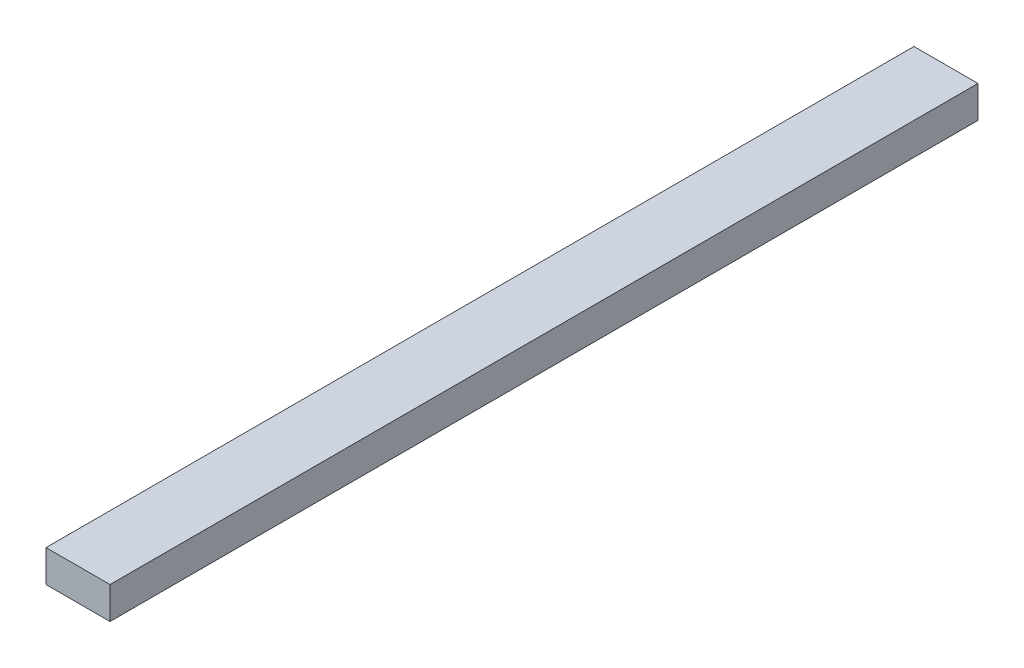
SolidWorks part; units mm, degrees
ref_plane "Front Plane" through (0, 0, 0) normal (0, 0, 1) x (1, 0, 0)
ref_plane "Top Plane" through (0, 0, 0) normal (0, 1, 0) x (1, 0, 0)
ref_plane "Right Plane" through (0, 0, 0) normal (1, 0, 0) x (0, 0, -1)
sketch "Sketch1" plane through (0, 0, 0) normal (0, 0, 1) x (1, 0, 0)
  line L1 (0, 0) -> (40, 0)
  line L2 (0, 0) -> (0, 20)
  line L3 (0, 20) -> (40, 20)
  line L4 (40, 0) -> (40, 20)
  dimension "D1" = 40
  dimension "D2" = 20
extrude "Boss-Extrude1" add sketch "Sketch1" along normal blind 542.2
